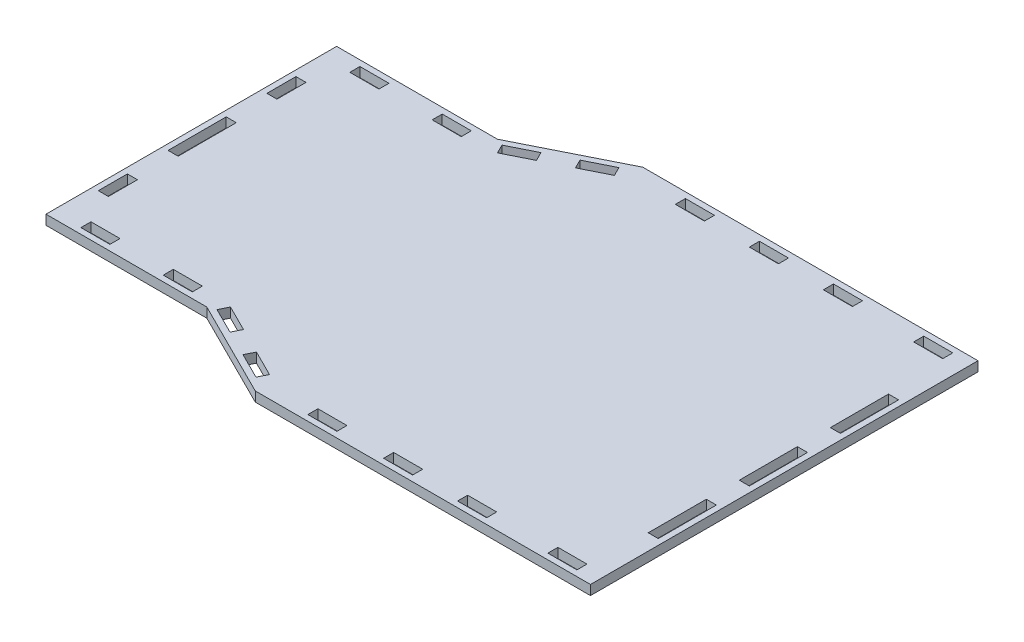
SolidWorks part; units mm, degrees
ref_plane "Front Plane" through (0, 0, 0) normal (0, 0, 1) x (1, 0, 0)
ref_plane "Top Plane" through (0, 0, 0) normal (0, 1, 0) x (1, 0, 0)
ref_plane "Right Plane" through (0, 0, 0) normal (1, 0, 0) x (0, 0, -1)
sketch "Sketch1" plane through (0, 0, 0) normal (0, 1, 0) x (1, 0, 0)
  line L0 (92.5145, -147.0199) -> (92.5145, 52.9801)
  line L1 (92.5145, 52.9801) -> (-80.4855, 52.9801)
  line L2 (-213.4855, -122.0199) -> (-130.4855, -122.0199)
  line L3 (-130.4855, -122.0199) -> (-80.4855, -147.0199)
  line L4 (-130.4855, 27.9801) -> (-213.4855, 27.9801)
  line L5 (-213.4855, 27.9801) -> (-213.4855, -122.0199)
  line L7 (-80.4855, -147.0199) -> (92.5145, -147.0199)
  line L8 (-80.4855, 52.9801) -> (-130.4855, 27.9801)
  line L9 (67.5145, 49.9801) -> (82.5145, 49.9801)
  line L10 (67.5145, 49.9801) -> (67.5145, 44.7801)
  line L11 (67.5145, 44.7801) -> (82.5145, 44.7801)
  line L12 (82.5145, 49.9801) -> (82.5145, 44.7801)
  line L13 (67.5145, 49.9801) -> (82.5145, 44.7801) construction
  line L14 (67.5145, 44.7801) -> (82.5145, 49.9801) construction
  line L15 (67.5145, -138.8199) -> (82.5145, -138.8199)
  line L16 (67.5145, -138.8199) -> (67.5145, -144.0199)
  line L17 (67.5145, -144.0199) -> (82.5145, -144.0199)
  line L18 (82.5145, -138.8199) -> (82.5145, -144.0199)
  line L19 (67.5145, -138.8199) -> (82.5145, -144.0199) construction
  line L20 (67.5145, -144.0199) -> (82.5145, -138.8199) construction
  line L21 (84.3145, 14.9801) -> (89.5145, 14.9801)
  line L22 (84.3145, 14.9801) -> (84.3145, -15.0199)
  line L23 (84.3145, -15.0199) -> (89.5145, -15.0199)
  line L24 (89.5145, 14.9801) -> (89.5145, -15.0199)
  line L25 (84.3145, 14.9801) -> (89.5145, -15.0199) construction
  line L26 (84.3145, -15.0199) -> (89.5145, 14.9801) construction
  line L27 (84.3145, -32.0199) -> (89.5145, -32.0199)
  line L28 (84.3145, -32.0199) -> (84.3145, -62.0199)
  line L29 (84.3145, -62.0199) -> (89.5145, -62.0199)
  line L30 (89.5145, -32.0199) -> (89.5145, -62.0199)
  line L31 (84.3145, -32.0199) -> (89.5145, -62.0199) construction
  line L32 (84.3145, -62.0199) -> (89.5145, -32.0199) construction
  line L33 (84.3145, -79.0199) -> (89.5145, -79.0199)
  line L34 (84.3145, -79.0199) -> (84.3145, -109.0199)
  line L35 (84.3145, -109.0199) -> (89.5145, -109.0199)
  line L36 (89.5145, -79.0199) -> (89.5145, -109.0199)
  line L37 (84.3145, -79.0199) -> (89.5145, -109.0199) construction
  line L38 (84.3145, -109.0199) -> (89.5145, -79.0199) construction
  line L39 (-17.2855, 49.9738) -> (-2.2855, 49.9738)
  line L40 (-17.2855, 49.9738) -> (-17.2855, 44.7738)
  line L41 (-17.2855, 44.7738) -> (-2.2855, 44.7738)
  line L42 (-2.2855, 49.9738) -> (-2.2855, 44.7738)
  line L43 (-17.2855, 49.9738) -> (-2.2855, 44.7738) construction
  line L44 (-17.2855, 44.7738) -> (-2.2855, 49.9738) construction
  line L45 (-55.4855, 49.9738) -> (-40.4855, 49.9738)
  line L46 (-55.4855, 49.9738) -> (-55.4855, 44.7738)
  line L47 (-55.4855, 44.7738) -> (-40.4855, 44.7738)
  line L48 (-40.4855, 49.9738) -> (-40.4855, 44.7738)
  line L49 (-55.4855, 49.9738) -> (-40.4855, 44.7738) construction
  line L50 (-55.4855, 44.7738) -> (-40.4855, 49.9738) construction
  line L56 (-155.9855, 24.9801) -> (-140.9855, 24.9801)
  line L61 (-155.9855, 24.9801) -> (-155.9855, 19.7801)
  line L62 (-155.9855, 19.7801) -> (-140.9855, 19.7801)
  line L63 (-140.9855, 24.9801) -> (-140.9855, 19.7801)
  line L64 (-155.9855, 24.9801) -> (-140.9855, 19.7801) construction
  line L65 (-155.9855, 19.7801) -> (-140.9855, 24.9801) construction
  line L66 (-198.4855, 24.9801) -> (-183.4855, 24.9801)
  line L67 (-198.4855, 24.9801) -> (-198.4855, 19.7801)
  line L68 (-198.4855, 19.7801) -> (-183.4855, 19.7801)
  line L69 (-183.4855, 24.9801) -> (-183.4855, 19.7801)
  line L70 (-198.4855, 24.9801) -> (-183.4855, 19.7801) construction
  line L71 (-198.4855, 19.7801) -> (-183.4855, 24.9801) construction
  line L72 (-210.4855, 3.9801) -> (-205.2855, 3.9801)
  line L73 (-210.4855, 3.9801) -> (-210.4855, -11.0199)
  line L74 (-210.4855, -11.0199) -> (-205.2855, -11.0199)
  line L75 (-205.2855, 3.9801) -> (-205.2855, -11.0199)
  line L76 (-210.4855, 3.9801) -> (-205.2855, -11.0199) construction
  line L77 (-210.4855, -11.0199) -> (-205.2855, 3.9801) construction
  line L78 (-205.2855, -32.0199) -> (-210.4855, -32.0199)
  line L79 (-205.2855, -32.0199) -> (-205.2855, -62.0199)
  line L80 (-205.2855, -62.0199) -> (-210.4855, -62.0199)
  line L81 (-210.4855, -32.0199) -> (-210.4855, -62.0199)
  line L82 (-205.2855, -32.0199) -> (-210.4855, -62.0199) construction
  line L83 (-205.2855, -62.0199) -> (-210.4855, -32.0199) construction
  line L84 (-205.2855, -83.0199) -> (-210.4855, -83.0199)
  line L85 (-205.2855, -83.0199) -> (-205.2855, -98.0199)
  line L86 (-205.2855, -98.0199) -> (-210.4855, -98.0199)
  line L87 (-210.4855, -83.0199) -> (-210.4855, -98.0199)
  line L88 (-205.2855, -83.0199) -> (-210.4855, -98.0199) construction
  line L89 (-205.2855, -98.0199) -> (-210.4855, -83.0199) construction
  line L94 (-56.3606, -138.8201) -> (-41.3606, -138.8201)
  line L95 (-41.3606, -144.0201) -> (-41.3606, -138.8201)
  line L96 (-56.3606, -144.0201) -> (-41.3606, -144.0201)
  line L97 (-56.3606, -144.0201) -> (-56.3606, -138.8201)
  line L106 (-155.9855, -113.8199) -> (-140.9855, -113.8199)
  line L107 (-140.9855, -119.0199) -> (-140.9855, -113.8199)
  line L108 (-155.9855, -119.0199) -> (-140.9855, -119.0199)
  line L109 (-155.9855, -119.0199) -> (-155.9855, -113.8199)
  line L110 (-198.4855, -113.8199) -> (-183.4855, -113.8199)
  line L111 (-183.4855, -119.0199) -> (-183.4855, -113.8199)
  line L112 (-198.4855, -119.0199) -> (-183.4855, -119.0199)
  line L113 (-198.4855, -119.0199) -> (-198.4855, -113.8199)
  line L114 (20.9145, 49.9801) -> (35.9145, 49.9801)
  line L119 (20.9145, 49.9801) -> (20.9145, 44.7801)
  line L120 (20.9145, 44.7801) -> (35.9145, 44.7801)
  line L121 (35.9145, 49.9801) -> (35.9145, 44.7801)
  line L122 (20.9145, 49.9801) -> (35.9145, 44.7801) construction
  line L123 (20.9145, 44.7801) -> (35.9145, 49.9801) construction
  line L124 (20.9145, -138.8199) -> (35.9145, -138.8199)
  line L125 (35.9145, -144.0199) -> (35.9145, -138.8199)
  line L126 (20.9145, -144.0199) -> (35.9145, -144.0199)
  line L127 (20.9145, -144.0199) -> (20.9145, -138.8199)
  line L128 (-17.2855, -138.8136) -> (-2.2855, -138.8136)
  line L129 (-2.2855, -144.0136) -> (-2.2855, -138.8136)
  line L130 (-17.2855, -144.0136) -> (-2.2855, -144.0136)
  line L131 (-17.2855, -144.0136) -> (-17.2855, -138.8136)
  line L132 (-110.9631, 28.5734) -> (-113.2883, 33.2237)
  line L133 (-113.2883, 33.2237) -> (-126.7047, 26.5155)
  line L134 (-86.4555, 46.6401) -> (-84.1303, 41.9898)
  line L135 (-84.1303, 41.9898) -> (-97.5467, 35.2816)
  line L136 (-97.5467, 35.2816) -> (-99.8719, 39.9319)
  line L137 (-99.8719, 39.9319) -> (-86.4555, 46.6401)
  line L138 (-126.7047, 26.5155) -> (-124.3795, 21.8652)
  line L139 (-124.3795, 21.8652) -> (-110.9631, 28.5734)
  line L140 (-99.8719, -133.9717) -> (-86.4555, -140.6799)
  line L141 (-97.5467, -129.3214) -> (-99.8719, -133.9717)
  line L142 (-84.1303, -136.0296) -> (-97.5467, -129.3214)
  line L143 (-86.4555, -140.6799) -> (-84.1303, -136.0296)
  line L144 (-124.3795, -115.905) -> (-110.9631, -122.6132)
  line L145 (-126.7047, -120.5553) -> (-124.3795, -115.905)
  line L146 (-113.2883, -127.2635) -> (-126.7047, -120.5553)
  line L147 (-110.9631, -122.6132) -> (-113.2883, -127.2635)
  point P2 (75.0145, 47.3801)
  point P13 (75.0145, -141.4199)
  point P18 (86.9145, -0.0199)
  point P23 (86.9145, -47.0199)
  point P28 (86.9145, -94.0199)
  point P33 (86.9145, -109.0199)
  point P34 (86.9145, 14.9801)
  point P35 (-9.7855, 47.3738)
  point P40 (-47.9855, 47.3738)
  point P45 (-190.9855, 22.3801)
  point P47 (-148.4855, 22.3801)
  point P58 (-213.4855, -47.0199)
  point P59 (92.5145, -47.0199)
  point P65 (-207.8855, -3.5199)
  point P70 (-207.8855, -47.0199)
  point P75 (-207.8855, -90.5199)
  point P110 (28.4145, 47.3801)
  point P117 (20.9145, 47.3801)
  dimension "D1" = 200
  dimension "D2" = 173
  dimension "D3" = 5.2
  dimension "D4" = 5.2
  dimension "D5" = 83
  dimension "D6" = 150
  dimension "D7" = 15
  dimension "D8" = 15
  dimension "D9" = 17.5
  dimension "D10" = 17.5
  dimension "D11" = 5.6
  dimension "D12" = 5.6
  dimension "D13" = 5.2
  dimension "D14" = 5.2
  dimension "D15" = 5.2
  dimension "D16" = 5.6
  dimension "D17" = 5.6
  dimension "D18" = 5.6
  dimension "D19" = 30
  dimension "D20" = 30
  dimension "D21" = 30
  dimension "D22" = 38
  dimension "D23" = 38
  dimension "D24" = 47
  dimension "D25" = 5.2
  dimension "D26" = 5.2
  dimension "D27" = 15
  dimension "D28" = 15
  dimension "D29" = 25
  dimension "D30" = 38.2
  dimension "D31" = 63.435
  dimension "D32" = 3.0008
  dimension "D33" = 5.1992
  dimension "D34" = 15
  dimension "D35" = 6.34
  dimension "D36" = 15
  dimension "D37" = 15
  dimension "D38" = 5.2
  dimension "D39" = 306
  dimension "D40" = 50
  dimension "D41" = 3
  dimension "D42" = 15
  dimension "D43" = 5.2
  dimension "D44" = 3
  dimension "D45" = 27.5
  dimension "D46" = 15
  dimension "D47" = 15
  dimension "D48" = 5.2
  dimension "D49" = 3
  dimension "D50" = 30
  dimension "D51" = 5.2
  dimension "D52" = 3
  dimension "D53" = 24
  dimension "D54" = 21
  dimension "D55" = 15
  dimension "D56" = 5.2
  dimension "D57" = 3
  dimension "D58" = 21
  dimension "D65" = 5.2
  dimension "D66" = 15
  dimension "D67" = 3
  dimension "D68" = 23.2
  dimension "D69" = 15
  dimension "D70" = 5.2
  dimension "D71" = 3
  dimension "D72" = 15
  dimension "D73" = 27.5
  dimension "D74" = 15
  dimension "D75" = 5.2
  dimension "D76" = 3
  dimension "D77" = 15
  dimension "D78" = 5.1992
extrude "Boss-Extrude1" add sketch "Sketch1" along normal blind 5
